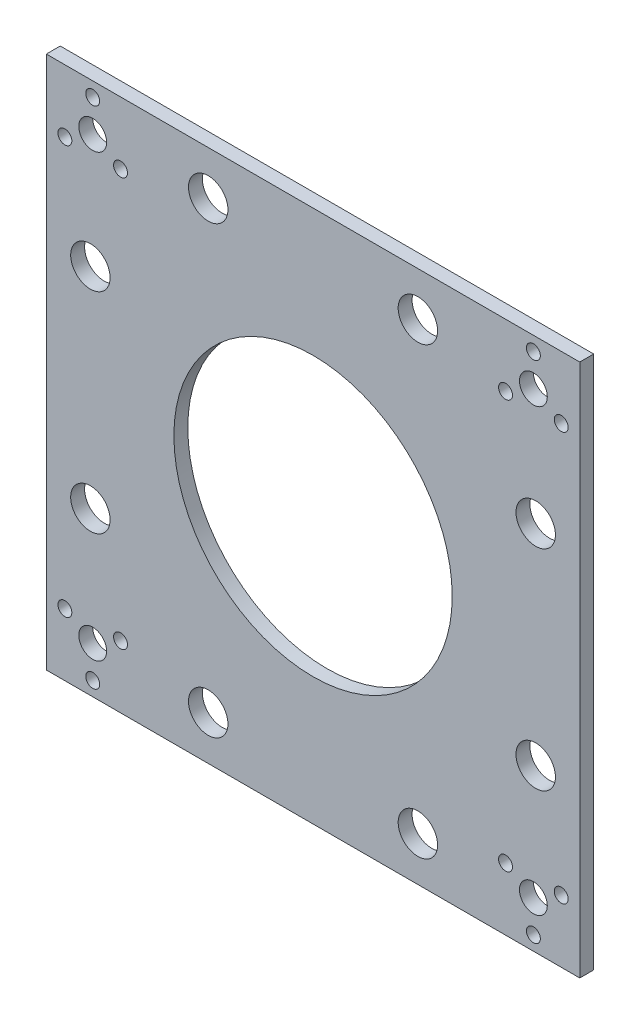
SolidWorks part; units mm, degrees
ref_plane "前视基准面" through (0, 0, 0) normal (0, 0, 1) x (1, 0, 0)
ref_plane "上视基准面" through (0, 0, 0) normal (0, 1, 0) x (1, 0, 0)
ref_plane "右视基准面" through (0, 0, 0) normal (1, 0, 0) x (0, 0, -1)
other "Configuration Table"
sketch "草图1" plane through (0, 0, 0) normal (0, 0, 1) x (1, 0, 0)
  line L1 (-57.5, 57.5) -> (57.5, 57.5)
  line L2 (-57.5, 57.5) -> (-57.5, -57.5)
  line L3 (-57.5, -57.5) -> (57.5, -57.5)
  line L4 (57.5, 57.5) -> (57.5, -57.5)
  line L5 (-57.5, 57.5) -> (57.5, -57.5) construction
  line L6 (-57.5, -57.5) -> (57.5, 57.5) construction
  line L7 (-47.5, -47.5) -> (47.5, -47.5) construction
  line L8 (-47.5, -47.5) -> (-47.5, 47.5) construction
  line L9 (-47.5, 47.5) -> (47.5, 47.5) construction
  line L10 (47.5, -47.5) -> (47.5, 47.5) construction
  line L11 (-47.5, -47.5) -> (47.5, 47.5) construction
  line L12 (-47.5, 47.5) -> (47.5, -47.5) construction
  circle A0 centre (0, 0) radius 30
  circle A1 centre (-47.5, 47.5) radius 3
  circle A2 centre (47.5, 47.5) radius 3
  circle A3 centre (47.5, -47.5) radius 3
  circle A4 centre (-47.5, -47.5) radius 3
  point P0 (0, 0)
  dimension "D3" = 60
  dimension "D6" = 6
  dimension "D1" = 115
  dimension "D2" = 115
  dimension "D4" = 95
  dimension "D5" = 95
extrude "凸台-拉伸1" add sketch "草图1" along normal blind 3
sketch "草图3" plane through (0, 0, 3) normal (0, 0, 1) x (1, 0, 0)
  line L1 (-47.5, 54.4282) -> (-53.5, 44.0359)
  line L2 (-53.5, 44.0359) -> (-41.5, 44.0359)
  line L3 (-41.5, 44.0359) -> (-47.5, 54.4282)
  circle A0 centre (-47.5, 47.5) radius 3.4641 construction
  circle A1 centre (-41.5, 44.0359) radius 1.5
  circle A2 centre (-53.5, 44.0359) radius 1.5
  circle A3 centre (-47.5, 54.4282) radius 1.5
  dimension "D3" = 3
  dimension "D1" = 12
extrude "切除-拉伸2" cut sketch "草图3" against normal through all contours L1 A2 L2 | L2 A1 L3 | L3 A1 L2 | L2 A2 L1 | L3 A3 L1 | L1 A3 L3
mirror "镜向3" about plane through (0, 0, 0) normal (1, 0, 0) of "切除-拉伸2"
mirror "镜向4" about plane through (0, 0, 0) normal (0, 1, 0) of "镜向3", "切除-拉伸2"
sketch "草图4" plane through (0, 0, 3) normal (0, 0, 1) x (1, 0, 0)
  line L0 (0, 57.5) -> (0, -57.5) construction
  line L1 (57.5, 57.5) -> (-57.5, 57.5) construction
  line L2 (-57.5, -57.5) -> (57.5, -57.5) construction
  line L3 (-57.5, 0) -> (57.5, 0) construction
  line L4 (-57.5, 57.5) -> (-57.5, -57.5) construction
  line L5 (57.5, -57.5) -> (57.5, 57.5) construction
  circle A0 centre (-22.6, 48) radius 4.25
  circle A1 centre (-48, 22.6) radius 4.25
  circle A2 centre (22.6, 48) radius 4.25
  circle A3 centre (48, 22.6) radius 4.25
  circle A4 centre (48, -22.6) radius 4.25
  circle A5 centre (22.6, -48) radius 4.25
  circle A6 centre (-48, -22.6) radius 4.25
  circle A7 centre (-22.6, -48) radius 4.25
  dimension "D1" = 45.2
  dimension "D2" = 96
  dimension "D3" = 8.5
  dimension "D4" = 8.5
  dimension "D5" = 96
  dimension "D6" = 45.2
extrude "切除-拉伸3" cut sketch "草图4" against normal up to surface (3 mm away) up to face at (-40, -44.0359, 0)
